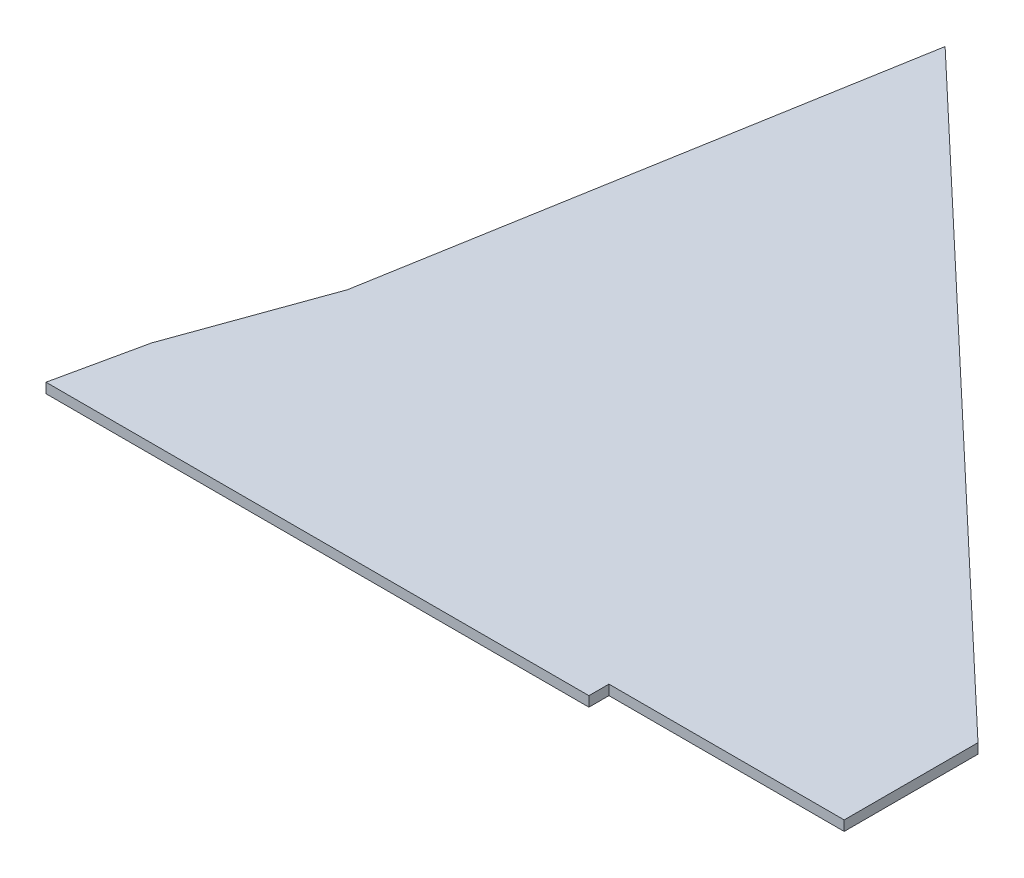
SolidWorks part; units mm, degrees
ref_plane "前视基准面" through (0, 0, 0) normal (0, 0, 1) x (1, 0, 0)
ref_plane "上视基准面" through (0, 0, 0) normal (0, 1, 0) x (1, 0, 0)
ref_plane "右视基准面" through (0, 0, 0) normal (1, 0, 0) x (0, 0, -1)
other "Configuration Table"
sketch "草图1" plane through (0, 0, 0) normal (0, 1, 0) x (1, 0, 0)
  line L0 (0, 0) -> (63.5515, -60.177) construction
  line L1 (63.5515, -60.177) -> (63.5515, -67.0349) construction
  line L2 (63.5515, -67.0349) -> (-14.2949, -67.0349) construction
  line L3 (-14.2949, -67.0349) -> (-9.1207, -52.6598) construction
  line L4 (-9.1207, -52.6598) -> (0, 0) construction
  line L5 (0.667, -2.0087) -> (62.5515, -60.6072)
  line L6 (62.5515, -60.6072) -> (62.5515, -66.0349)
  line L8 (-12.8722, -66.0349) -> (-8.1503, -52.9164)
  line L9 (-8.1503, -52.9164) -> (0.667, -2.0087)
  line L10 (62.5515, -66.0349) -> (-12.8722, -66.0349) construction
  line L11 (-14.2949, -67.0349) -> (-16.4485, -76.9805) construction
  line L12 (-16.4485, -76.9805) -> (40.0455, -76.9805) construction
  line L13 (40.0455, -76.9805) -> (40.0455, -74.9805) construction
  line L14 (40.0455, -74.9805) -> (63.5515, -74.9805) construction
  line L15 (63.5515, -74.9805) -> (63.5515, -67.0349) construction
  line L16 (-12.8722, -66.0349) -> (-13.2321, -67.0349)
  line L18 (-13.3176, -67.2465) -> (-15.2088, -75.9805)
  line L19 (-15.2088, -75.9805) -> (39.0455, -75.9805)
  line L20 (39.0455, -75.9805) -> (39.0455, -73.9805)
  line L21 (39.0455, -73.9805) -> (62.5515, -73.9805)
  line L22 (62.5515, -73.9805) -> (62.5515, -67.0349)
  line L23 (-13.3176, -67.2465) -> (-13.2321, -67.0349)
  line L24 (62.5515, -66.0349) -> (62.5515, -67.0349)
  dimension "D1" = 87.5218
  dimension "D2" = 6.8579
  dimension "D3" = 77.8464
  dimension "D4" = 15.278
  dimension "D5" = 53.4438
  dimension "D6" = 5.1742
  dimension "D8" = 10.1761
  dimension "D9" = 56.494
  dimension "D10" = 2
  dimension "D11" = 23.506
  dimension "D12" = 1
  dimension "D7" = 1
extrude "凸台-拉伸2" add sketch "草图1" along normal blind 1
sketch "草图2" plane through (0, 0, 0) normal (0, -1, 0) x (1, 0, 0)
  line L0 (-8.1503, 52.9164) -> (54.4294, 52.9164) construction
  line L1 (62.5515, 60.6072) -> (0.667, 2.0087) construction
  text T0 "Part 1" font "@Arial Unicode MS" height 4
extrude "凸台-拉伸3" add sketch "草图2" along normal blind 0.2
